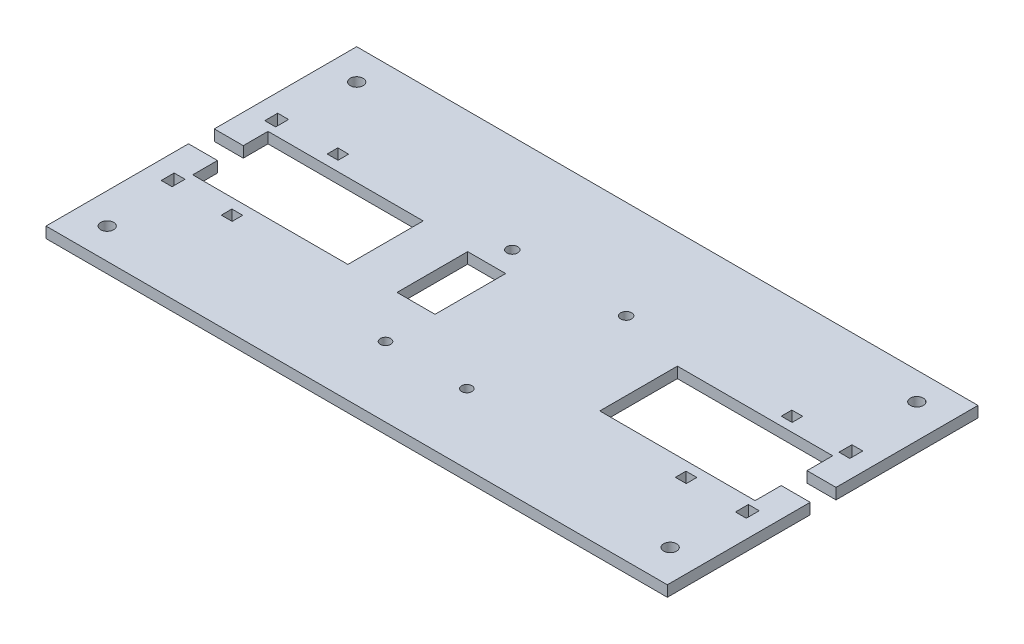
SolidWorks part; units mm, degrees
ref_plane "Front Plane" through (0, 0, 0) normal (0, 0, 1) x (1, 0, 0)
ref_plane "Top Plane" through (0, 0, 0) normal (0, 1, 0) x (1, 0, 0)
ref_plane "Right Plane" through (0, 0, 0) normal (1, 0, 0) x (0, 0, -1)
sketch "Sketch1" plane through (0, 0, 0) normal (0, 1, 0) x (1, 0, 0)
  line L1 (-216.1549, 23.7753) -> (88.6451, 23.7753)
  line L2 (-216.1549, 23.7753) -> (-216.1549, -128.6247)
  line L3 (-216.1549, -128.6247) -> (88.6451, -128.6247)
  line L4 (88.6451, 23.7753) -> (88.6451, -128.6247)
  dimension "D1" = 304.8
  dimension "D2" = 152.4
extrude "Boss-Extrude1" add sketch "Sketch1" along normal blind 5.334
sketch "Sketch2" plane through (0, 5.334, 0) normal (0, 1, 0) x (1, 0, 0)
  line L0 (-216.1549, -128.6247) -> (88.6451, -128.6247) construction
  line L1 (-216.1549, 23.7753) -> (-216.1549, -128.6247) construction
  line L2 (-64.6105, 23.7753) -> (-63.7549, -128.6247) construction
  line L3 (88.6451, 23.7753) -> (-216.1549, 23.7753) construction
  line L4 (-216.1549, -52.4247) -> (88.6451, -52.4247) construction
  line L5 (88.6451, -128.6247) -> (88.6451, 23.7753) construction
  circle A0 centre (-201.1549, -113.6247) radius 3.175
  circle A1 centre (-201.1549, 8.7753) radius 3.175
  circle A2 centre (73.468, -112.0829) radius 3.175
  circle A3 centre (72.0937, 10.3094) radius 3.175
  dimension "D1" = 15
  dimension "D3" = 6.35
  dimension "D2" = 15
extrude "Cut-Extrude1" cut sketch "Sketch2" against normal blind 10
sketch "Sketch4" plane through (0, 5.334, 0) normal (0, 1, 0) x (1, 0, 0)
  circle A0 centre (-91.6879, -24.3578) radius 2.677
  circle A1 centre (-35.688, -24.4917) radius 2.6657
  circle A2 centre (-43.8554, -94.4724) radius 2.53
  circle A3 centre (-83.8553, -94.3767) radius 2.5353
extrude "Cut-Extrude3" cut sketch "Sketch4" against normal through all
sketch "Sketch5" plane through (0, 5.334, 0) normal (0, 1, 0) x (1, 0, 0)
  line L0 (74.4211, -74.6497) -> (79.7551, -74.6497) construction
  line L1 (-201.9309, -80.9997) -> (-207.2649, -80.9997)
  line L2 (-201.9309, -80.9997) -> (-201.9309, -74.6497)
  line L3 (-201.9309, -74.6497) -> (-207.2649, -74.6497)
  line L4 (-207.2649, -80.9997) -> (-207.2649, -74.6497)
  line L5 (-201.9309, -30.1997) -> (-207.2649, -30.1997)
  line L6 (-201.9309, -30.1997) -> (-201.9309, -23.8497)
  line L7 (-201.9309, -23.8497) -> (-207.2649, -23.8497)
  line L8 (-207.2649, -30.1997) -> (-207.2649, -23.8497)
  line L9 (-172.4669, -29.0567) -> (-177.8009, -29.0567)
  line L10 (-172.4669, -29.0567) -> (-172.4669, -23.8497)
  line L11 (-172.4669, -23.8497) -> (-177.8009, -23.8497)
  line L12 (-177.8009, -29.0567) -> (-177.8009, -23.8497)
  line L13 (-172.4669, -80.9997) -> (-177.8009, -80.9997)
  line L14 (-172.4669, -80.9997) -> (-172.4669, -75.7927)
  line L15 (-172.4669, -75.7927) -> (-177.8009, -75.7927)
  line L16 (-177.8009, -80.9997) -> (-177.8009, -75.7927)
  line L17 (79.7551, -80.9997) -> (74.4211, -80.9997)
  line L18 (79.7551, -80.9997) -> (79.7551, -74.6497)
  line L19 (79.7551, -74.6497) -> (74.4211, -74.6497)
  line L20 (74.4211, -80.9997) -> (74.4211, -74.6497)
  line L22 (50.2911, -80.9997) -> (44.9571, -80.9997)
  line L23 (50.2911, -80.9997) -> (50.2911, -75.7927)
  line L24 (50.2911, -75.7927) -> (44.9571, -75.7927)
  line L25 (44.9571, -80.9997) -> (44.9571, -75.7927)
  line L26 (79.7551, -30.1997) -> (74.4211, -30.1997)
  line L27 (79.7551, -30.1997) -> (79.7551, -23.8497)
  line L28 (79.7551, -23.8497) -> (74.4211, -23.8497)
  line L29 (74.4211, -30.1997) -> (74.4211, -23.8497)
  line L30 (50.2911, -29.0567) -> (44.9571, -29.0567)
  line L31 (50.2911, -29.0567) -> (50.2911, -23.8497)
  line L32 (50.2911, -23.8497) -> (44.9571, -23.8497)
  line L33 (44.9571, -29.0567) -> (44.9571, -23.8497)
extrude "Cut-Extrude4" cut sketch "Sketch5" against normal through all
sketch "Sketch7" plane through (0, 5.334, 0) normal (0, 1, 0) x (1, 0, 0)
  line L0 (74.4211, -74.6497) -> (74.4211, -30.1997) construction
sketch "Sketch8" plane through (0, 5.334, 0) normal (0, 1, 0) x (1, 0, 0)
  line L0 (74.4211, -74.6497) -> (74.4211, -30.1997) construction
  line L1 (74.4211, -35.2797) -> (-1.7789, -35.2797)
  line L2 (74.4211, -35.2797) -> (74.4211, -69.5697)
  line L3 (74.4211, -69.5697) -> (-1.7789, -69.5697)
  line L4 (-1.7789, -35.2797) -> (-1.7789, -69.5697)
  line L5 (74.4211, -35.2797) -> (-1.7789, -35.2797) construction
extrude "Cut-Extrude5" cut sketch "Sketch8" against normal through all
sketch "Sketch10" plane through (0, 5.334, 0) normal (0, 1, 0) x (1, 0, 0)
  line L1 (-1.7789, -69.5697) -> (74.4211, -69.5697)
  line L2 (-1.7789, -69.5697) -> (-1.7789, -71.3479)
  line L3 (-1.7789, -71.3479) -> (74.4211, -71.3479)
  line L4 (74.4211, -69.5697) -> (74.4211, -71.3479)
  line L5 (-1.7789, -35.2797) -> (74.4211, -35.2797)
  line L6 (-1.7789, -35.2797) -> (-1.7789, -33.2603)
  line L7 (-1.7789, -33.2603) -> (74.4211, -33.2603)
  line L8 (74.4211, -35.2797) -> (74.4211, -33.2603)
extrude "Cut-Extrude7" cut sketch "Sketch10" against normal through all
sketch "Sketch11" plane through (0, 5.334, 0) normal (0, 1, 0) x (1, 0, 0)
  line L0 (-201.9309, -74.6497) -> (-201.9309, -70.8843) construction
  line L1 (-201.9309, -30.1997) -> (-201.9309, -33.9345) construction
  line L3 (-201.9309, -70.8843) -> (-125.8098, -70.8843)
  line L4 (-201.9309, -70.8843) -> (-201.9309, -33.9345)
  line L5 (-201.9309, -33.9345) -> (-125.8098, -33.9345)
  line L6 (-125.8098, -70.8843) -> (-125.8098, -33.9345)
extrude "Cut-Extrude8" cut sketch "Sketch11" against normal through all
sketch "Sketch12" plane through (0, 5.334, 0) normal (0, 1, 0) x (1, 0, 0)
  line L1 (-201.9309, -33.9345) -> (-201.9309, -70.8843) construction
  line L2 (-201.9309, -58.7174) -> (-201.9309, -46.0785)
  line L3 (-216.1549, 23.7753) -> (-216.1549, -128.6247) construction
  line L4 (-201.9309, -58.7174) -> (-216.1549, -58.7174)
  line L6 (-201.9309, -46.0785) -> (-216.1549, -46.0785)
  line L7 (-216.1549, -58.7174) -> (-216.1549, -46.0785)
extrude "Cut-Extrude9" cut sketch "Sketch12" against normal through all
sketch "Sketch13" plane through (0, 5.334, 0) normal (0, 1, 0) x (1, 0, 0)
  line L1 (-101.8614, -70.713) -> (-83.2341, -70.713)
  line L2 (-101.8614, -70.713) -> (-101.8614, -36.0591)
  line L3 (-101.8614, -36.0591) -> (-83.2341, -36.0591)
  line L4 (-83.2341, -70.713) -> (-83.2341, -36.0591)
extrude "Cut-Extrude10" cut sketch "Sketch13" against normal through all
sketch "Sketch14" plane through (0, 5.334, 0) normal (0, 1, 0) x (1, 0, 0)
  line L0 (74.4211, -52.3041) -> (74.4211, -58.5394)
  line L1 (74.4211, -71.3479) -> (74.4211, -33.2603) construction
  line L2 (74.4211, -58.5394) -> (88.6451, -58.5394)
  line L3 (88.6451, -128.6247) -> (88.6451, 23.7753) construction
  line L4 (88.6451, -58.5394) -> (88.6451, -45.8749)
  line L5 (88.6451, -45.8749) -> (74.4211, -45.8749)
  line L6 (74.4211, -45.8749) -> (74.4211, -52.3041)
extrude "Cut-Extrude11" cut sketch "Sketch14" against normal through all
